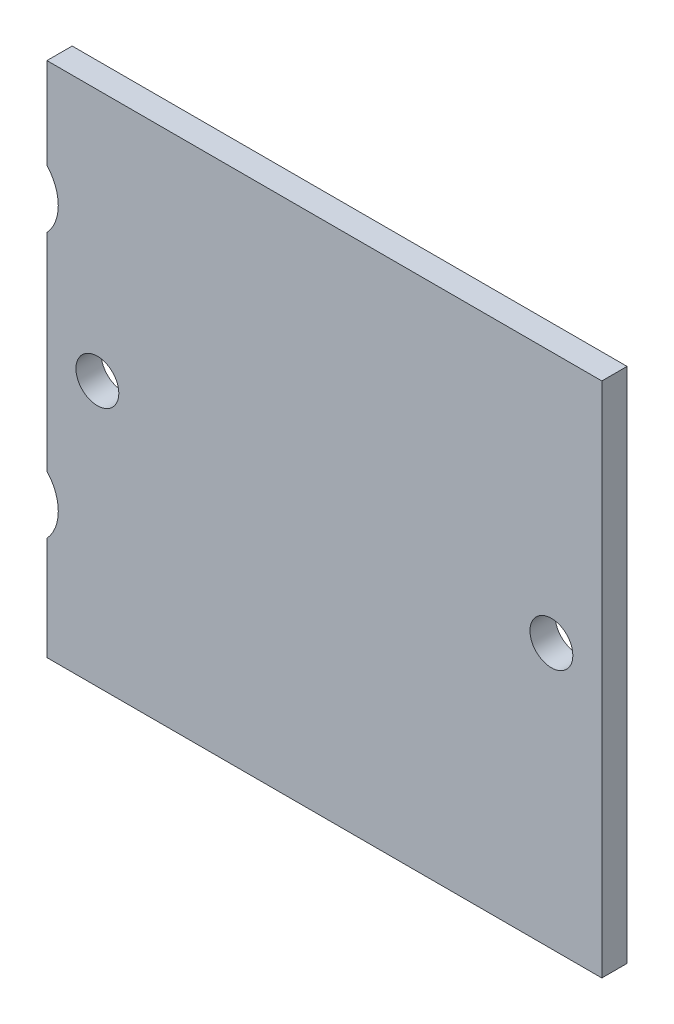
SolidWorks part; units mm, degrees
other "Relay Mounting Tray"
ref_plane "Front Plane" through (0, 0, 0) normal (0, 0, 1) x (1, 0, 0)
ref_plane "Top Plane" through (0, 0, 0) normal (0, 1, 0) x (1, 0, 0)
ref_plane "Right Plane" through (0, 0, 0) normal (1, 0, 0) x (0, 0, -1)
sketch3d "Main Profile Sketch datum points"
  point P0 (0, 0, 50.5)
  point P1 (10, 0, 50.5)
  point P2 (0, 10, 50.5)
ref_plane "Main Profile Sketch plane" through (0, 0, 50.5) normal (0, 0, 1) x (1, 0, 0)
sketch "Main Profile Sketch" plane through (0, 0, 50.5) normal (0, 0, 1) x (1, 0, 0)
  line L0 (178, 8.1957) -> (178, -8.1957)
  line L1 (178, 20) -> (178, 12.8043)
  line L2 (178, 20) -> (222, 20)
  line L3 (222, 20) -> (222, -21)
  line L4 (178, -21) -> (222, -21)
  line L5 (178, -12.8043) -> (178, -21)
  arc A0 (178, -12.8043) -> (178, -8.1957) centre (175.5, -10.5) ccw
  arc A1 (178, 8.1957) -> (178, 12.8043) centre (175.5, 10.5) ccw
  circle A2 centre (182, 0) radius 1.7
  circle A3 centre (218, 0) radius 1.7
extrude "Main Extrusion" add sketch "Main Profile Sketch" against normal blind 2 separate body
